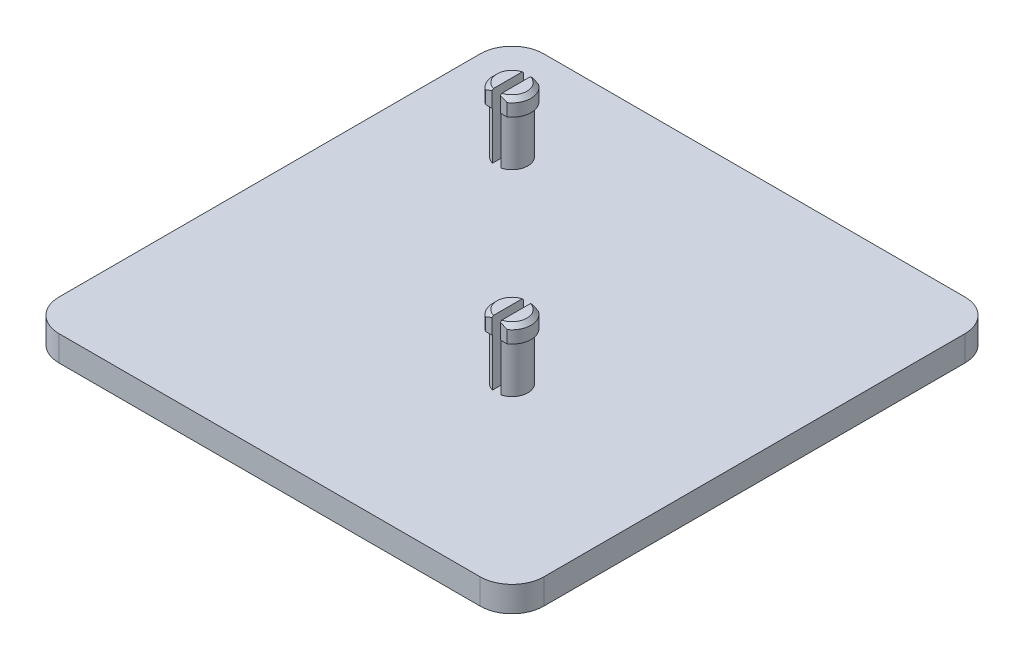
SolidWorks part; units mm, degrees
ref_plane "Front Plane" through (0, 0, 0) normal (0, 0, 1) x (1, 0, 0)
ref_plane "Top Plane" through (0, 0, 0) normal (0, 1, 0) x (1, 0, 0)
ref_plane "Right Plane" through (0, 0, 0) normal (1, 0, 0) x (0, 0, -1)
sketch "Base Profile" plane through (0, 0, 0) normal (0, 1, 0) x (1, 0, 0)
  line L1 (-38.1, -38.1) -> (38.1, -38.1)
  line L2 (-38.1, -38.1) -> (-38.1, 38.1)
  line L3 (-38.1, 38.1) -> (38.1, 38.1)
  line L4 (38.1, -38.1) -> (38.1, 38.1)
  line L5 (-38.1, -38.1) -> (38.1, 38.1) construction
  line L6 (-38.1, 38.1) -> (38.1, -38.1) construction
  point P0 (0, 0)
  dimension "D1" = 76.2
  dimension "D2" = 76.2
extrude "Base" add sketch "Base Profile" along normal mid plane 4
sketch "Connector Profile" plane through (0, 2, 0) normal (0, 1, 0) x (1, 0, 0)
  line L0 (-21.59, 21.59) -> (9.3021, -9.3021) construction
  line L1 (-38.1, -38.1) -> (38.1, -38.1) construction
  line L2 (38.1, 38.1) -> (-38.1, 38.1) construction
  line L4 (-38.1, 38.1) -> (-38.1, -38.1) construction
  circle A0 centre (-21.59, 21.59) radius 2.5
  circle A1 centre (9.3021, -9.3021) radius 2.5
  dimension "D1" = 5
  dimension "D2" = 5
  dimension "D5" = 16.51
  dimension "D6" = 16.51
  dimension "D3" = 43.688
  dimension "D4" = 45
extrude "Connector Body" add sketch "Connector Profile" along normal blind 7.5
sketch "Head Profile" plane through (0, 9.5, 0) normal (0, 1, 0) x (1, 0, 0)
  circle A0 centre (-21.59, 21.59) radius 3
  circle A1 centre (9.3021, -9.3021) radius 3
  circle A2 centre (-21.59, 21.59) radius 2.5 construction
  circle A3 centre (9.3021, -9.3021) radius 2.5 construction
  dimension "D1" = 6
  dimension "D2" = 6
extrude "Connector Head" add sketch "Head Profile" along normal blind 2.6
chamfer "Connector Head Chamfer" distance 0.65 angle 45 2 edges at (-21.59, 12.1, -18.59) (9.3021, 12.1, 12.3021)
sketch "Gap Profile" plane through (0, 12.1, 0) normal (0, 1, 0) x (1, 0, 0)
  line L0 (-22.24, 24.5187) -> (-22.24, 18.6613)
  line L1 (-20.94, 24.5187) -> (-20.94, 18.6613)
  line L2 (-22.24, 21.59) -> (-20.94, 21.59) construction
  line L3 (8.6521, -6.3733) -> (8.6521, -12.2308)
  line L4 (9.9521, -6.3733) -> (9.9521, -12.2308)
  line L5 (8.6521, -9.3021) -> (9.9521, -9.3021) construction
  circle A0 centre (-21.59, 21.59) radius 3 construction
  arc A1 (-20.94, 24.5187) -> (-22.24, 24.5187) centre (-21.59, 21.59) ccw
  circle A2 centre (9.3021, -9.3021) radius 3 construction
  arc A3 (9.9521, -6.3733) -> (8.6521, -6.3733) centre (9.3021, -9.3021) ccw
  arc A4 (8.6521, -12.2308) -> (9.9521, -12.2308) centre (9.3021, -9.3021) ccw
  arc A5 (-22.24, 18.6613) -> (-20.94, 18.6613) centre (-21.59, 21.59) ccw
  dimension "D1" = 1.3
  dimension "D2" = 1.3
extrude "Connector Gap" cut sketch "Gap Profile" against normal up to surface (10.1 mm away) up to face at (-21.59, 2, -24.09)
sketch "Trim Profile" plane through (0, 12.1, 0) normal (0, 1, 0) x (1, 0, 0)
  line L0 (7.6067, -6.8271) -> (10.9975, -6.8271)
  line L1 (9.3021, -6.8271) -> (9.3021, -11.7771) construction
  line L2 (7.6067, -11.7771) -> (10.9975, -11.7771)
  line L3 (-23.2854, 24.065) -> (-19.8946, 24.065)
  line L4 (-23.2854, 19.115) -> (-19.8946, 19.115)
  line L5 (-21.59, 24.065) -> (-21.59, 19.115) construction
  arc A0 (7.6067, -11.7771) -> (10.9975, -11.7771) centre (9.3021, -9.3021) ccw
  arc A1 (9.9521, -12.2308) -> (9.9521, -6.3733) centre (9.3021, -9.3021) ccw construction
  arc A2 (10.9975, -6.8271) -> (7.6067, -6.8271) centre (9.3021, -9.3021) ccw
  arc A3 (-23.2854, 19.115) -> (-19.8946, 19.115) centre (-21.59, 21.59) ccw
  arc A4 (-20.94, 18.6613) -> (-20.94, 24.5187) centre (-21.59, 21.59) ccw construction
  arc A5 (-22.24, 24.5187) -> (-22.24, 18.6613) centre (-21.59, 21.59) ccw construction
  arc A6 (-19.8946, 24.065) -> (-23.2854, 24.065) centre (-21.59, 21.59) ccw
  dimension "D2" = 4.95
  dimension "D1" = 4.95
extrude "Trim Head" cut sketch "Trim Profile" against normal up to surface (10.1 mm away)
fillet "Round Edge" radius 5 4 edges at (38.1, 0, -38.1) (-38.1, 0, -38.1) (-38.1, 0, 38.1) (38.1, 0, 38.1)
